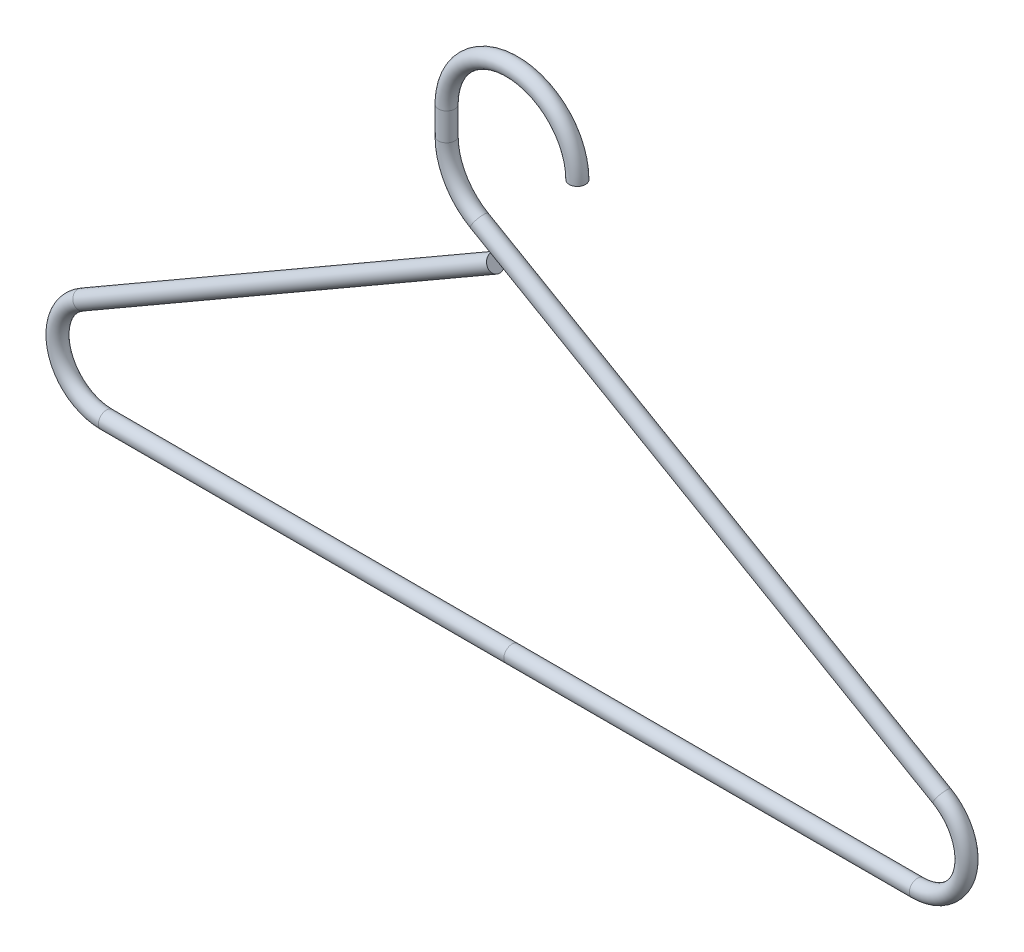
SolidWorks part; units mm, degrees
material "1060 Alloy"
ref_plane "Front Plane" through (0, 0, 0) normal (0, 0, 1) x (1, 0, 0)
ref_plane "Top Plane" through (0, 0, 0) normal (0, 1, 0) x (1, 0, 0)
ref_plane "Right Plane" through (0, 0, 0) normal (1, 0, 0) x (0, 0, -1)
sketch "Sketch1" plane through (0, 0, 0) normal (0, 0, 1) x (1, 0, 0)
  line L0 (0, 0) -> (157.5044, 0)
  line L1 (167.0294, 35.5478) -> (-12.7, 139.3146)
  line L2 (-25.4, 161.3117) -> (-25.4, 172.047)
  line L3 (0, 0) -> (0, 172.047) construction
  line L4 (-25.4, 172.047) -> (25.4, 172.047) construction
  line L5 (0, 0) -> (-157.5044, 0)
  line L6 (-167.0294, 35.5478) -> (-6.35, 128.3161)
  arc A0 (-25.4, 172.047) -> (25.4, 172.047) centre (0, 172.047) cw
  arc A1 (-12.7, 139.3146) -> (-25.4, 161.3117) centre (0, 161.3117) cw
  arc A2 (-167.0294, 35.5478) -> (-157.5044, 0) centre (-157.5044, 19.05) ccw
  arc A3 (167.0294, 35.5478) -> (157.5044, 0) centre (157.5044, 19.05) cw
  point P11 (-25.4, 146.647)
  point P14 (-228.6, 0)
  point P17 (228.6, 0)
  dimension "D1" = 25.4
  dimension "D7" = 25.4
  dimension "D8" = 19.05
  dimension "D2" = 30
  dimension "D3" = 30
  dimension "D4" = 25.4
  dimension "D5" = 6.35
  dimension "D6" = 457.2
sketch "Sketch2" plane through (0, 0, 0) normal (1, 0, 0) x (0, 0, -1)
  line L1 (-3.582, -1.8629) -> (3.582, -1.8629)
  line L2 (-3.582, -1.8629) -> (-3.582, 1.8629)
  line L3 (-3.582, 1.8629) -> (3.582, 1.8629)
  line L4 (3.582, -1.8629) -> (3.582, 1.8629)
  line L5 (-3.582, -1.8629) -> (3.582, 1.8629) construction
  line L6 (-3.582, 1.8629) -> (3.582, -1.8629) construction
  point P0 (0, 0)
  point P7 (-3.582, 1.8629)
sweep "Sweep2" add path "Sketch1" circular profile diameter 6.35 parameters "D3"=6.35
equation "\"D2@Sketch1\" = 30"
equation "\"D3@Sketch1\" = \"D2@Sketch1\""
